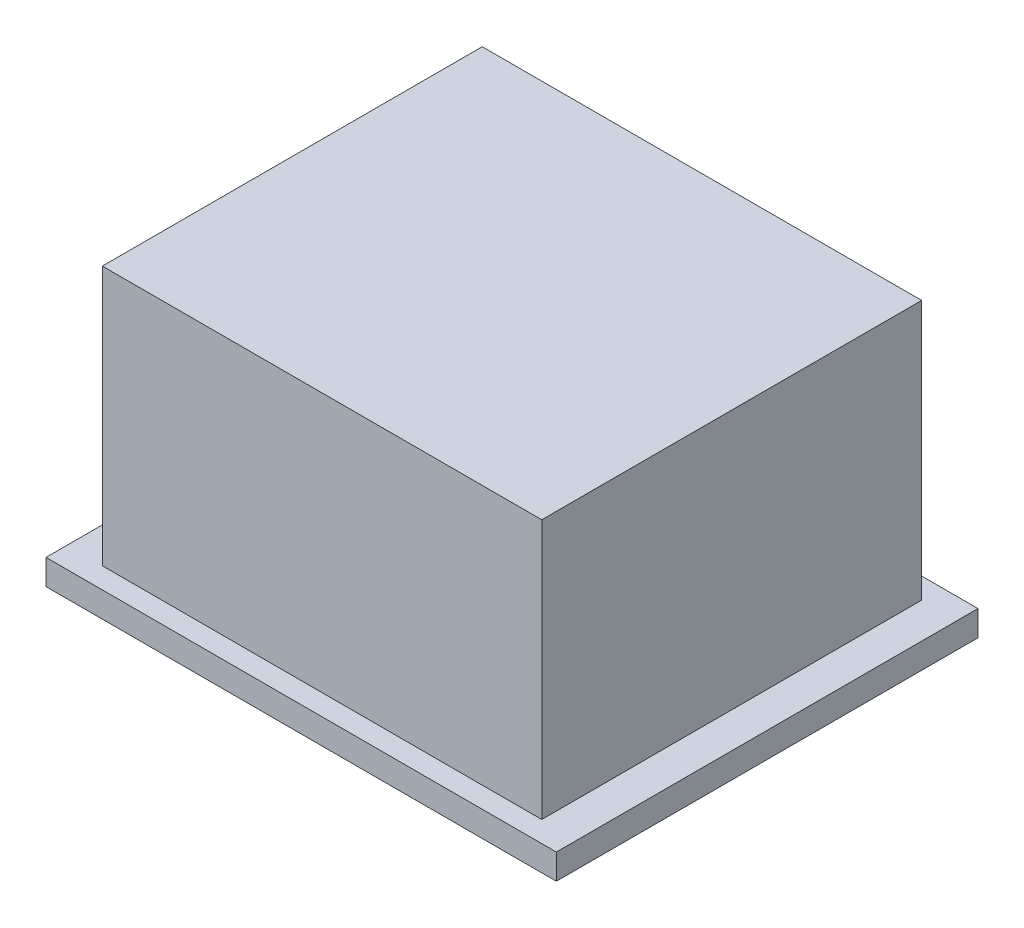
SolidWorks part; units mm, degrees
ref_plane "Front Plane" through (0, 0, 0) normal (0, 0, 1) x (1, 0, 0)
ref_plane "Top Plane" through (0, 0, 0) normal (0, 1, 0) x (1, 0, 0)
ref_plane "Right Plane" through (0, 0, 0) normal (1, 0, 0) x (0, 0, -1)
sketch "Sketch1" plane through (0, 0, 0) normal (0, 1, 0) x (1, 0, 0)
  line L1 (0, 0) -> (40.3, 0)
  line L2 (0, 0) -> (0, 33.3)
  line L3 (0, 33.3) -> (40.3, 33.3)
  line L4 (40.3, 0) -> (40.3, 33.3)
  dimension "D1" = 40.3
  dimension "D2" = 33.3
extrude "Boss-Extrude1" add sketch "Sketch1" along normal blind 2
sketch "Sketch2" plane through (0, 2, 0) normal (0, 1, 0) x (1, 0, 0)
  line L0 (20.15, 33.3) -> (20.15, 0) construction
  line L1 (40.3, 33.3) -> (0, 33.3) construction
  line L2 (0, 0) -> (40.3, 0) construction
  line L4 (2.8, 1.65) -> (37.5, 1.65)
  line L5 (2.8, 1.65) -> (2.8, 31.65)
  line L6 (2.8, 31.65) -> (37.5, 31.65)
  line L7 (37.5, 1.65) -> (37.5, 31.65)
  line L8 (2.8, 1.65) -> (37.5, 31.65) construction
  line L9 (2.8, 31.65) -> (37.5, 1.65) construction
  point P6 (20.15, 16.65)
  dimension "D1" = 34.7
  dimension "D2" = 30
extrude "Boss-Extrude2" add sketch "Sketch2" along normal blind 20.5
